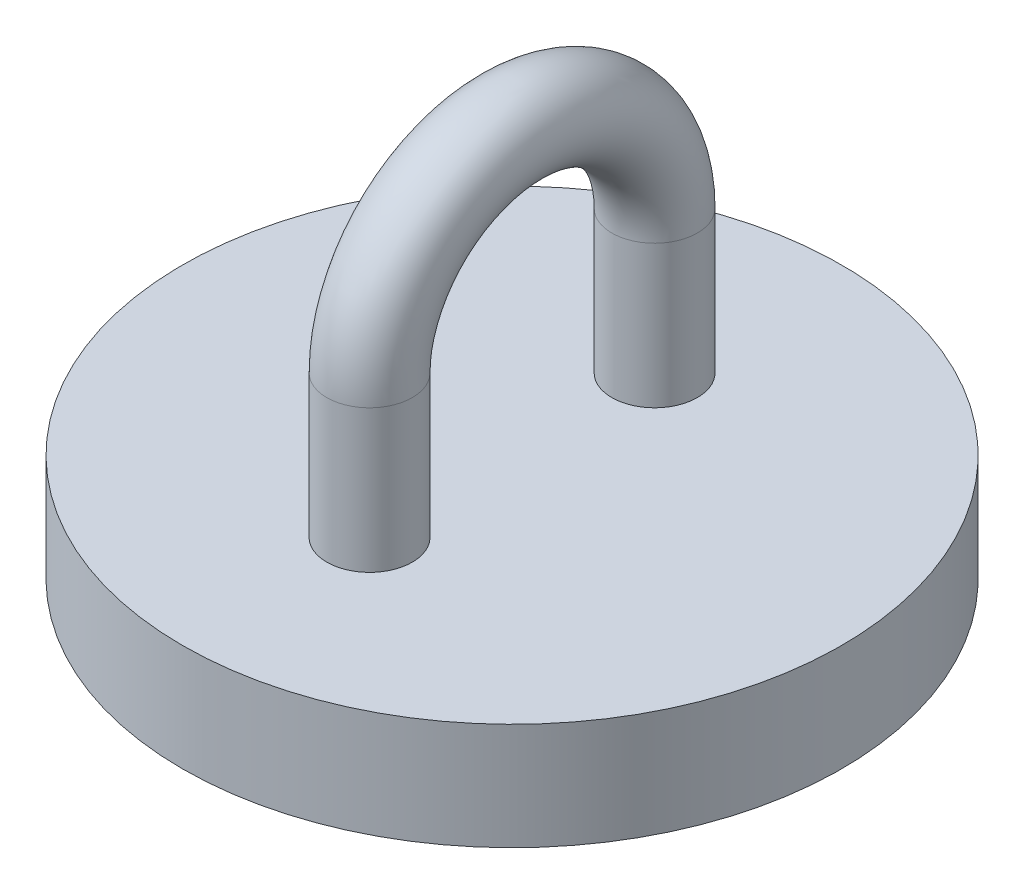
SolidWorks part; units mm, degrees
ref_plane "Front Plane" through (0, 0, 0) normal (0, 0, 1) x (1, 0, 0)
ref_plane "Top Plane" through (0, 0, 0) normal (0, 1, 0) x (1, 0, 0)
ref_plane "Right Plane" through (0, 0, 0) normal (1, 0, 0) x (0, 0, -1)
sketch "Sketch1" plane through (0, 0, 0) normal (0, 1, 0) x (1, 0, 0)
  circle A0 centre (0, 0) radius 9.25
  dimension "D1" = 18.5
extrude "Boss-Extrude1" add sketch "Sketch1" along normal blind 3
sketch "Sketch2" plane through (0, 3, 0) normal (0, 1, 0) x (1, 0, 0)
  line L0 (0, -4) -> (0, 0)
  circle A0 centre (0, -4) radius 1.2
  dimension "D1" = 2.4
  dimension "D2" = 4
sketch "Sketch3" plane through (0, 0, 0) normal (1, 0, 0) x (0, 0, -1)
  line L0 (-4, 3) -> (-4, 7)
  line L1 (-2.8, 3) -> (-5.2, 3) construction
  line L2 (4, 7) -> (4, 3)
  line L3 (9.25, 3) -> (-9.25, 3) construction
  arc A0 (4, 7) -> (-4, 7) centre (0, 7) ccw
  dimension "D1" = 4
  dimension "D2" = 4
sweep "Sweep1" add profiles "Sketch2" path "Sketch3"
